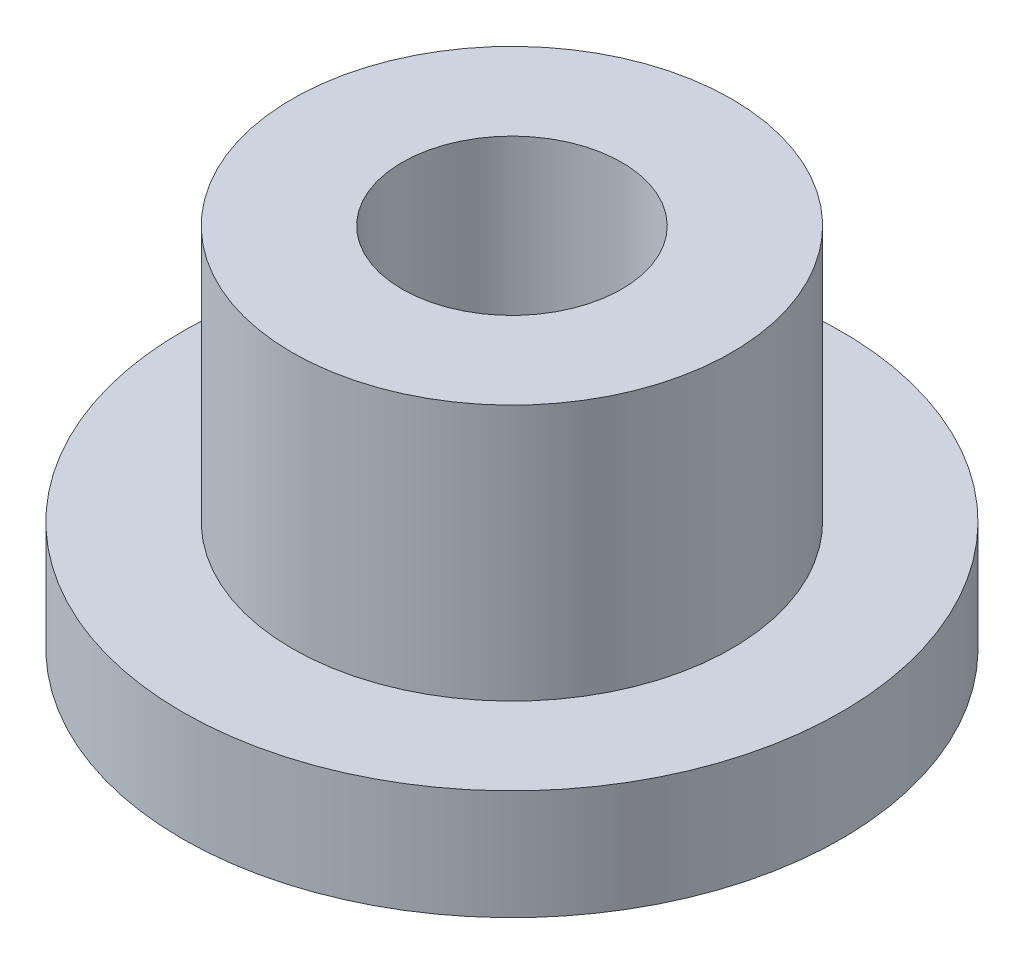
SolidWorks part; units mm, degrees
material "latón"
ref_plane "Alzado" through (0, 0, 0) normal (0, 0, 1) x (1, 0, 0)
ref_plane "Planta" through (0, 0, 0) normal (0, 1, 0) x (1, 0, 0)
ref_plane "Vista lateral" through (0, 0, 0) normal (1, 0, 0) x (0, 0, -1)
sketch "Croquis1" plane through (0, 0, 0) normal (0, 1, 0) x (1, 0, 0)
  circle A0 centre (0, 0) radius 4.5
  circle A1 centre (0, 0) radius 1.5
  dimension "D1" = 3
  dimension "D2" = 9
extrude "Saliente-Extruir1" add sketch "Croquis1" along normal blind 1.5
sketch "Croquis2" plane through (0, 1.5, 0) normal (0, 1, 0) x (1, 0, 0)
  circle A0 centre (0, 0) radius 1.5
  circle A1 centre (0, 0) radius 3
  dimension "D1" = 3
  dimension "D2" = 6
extrude "Saliente-Extruir2" add sketch "Croquis2" along normal blind 3.5
